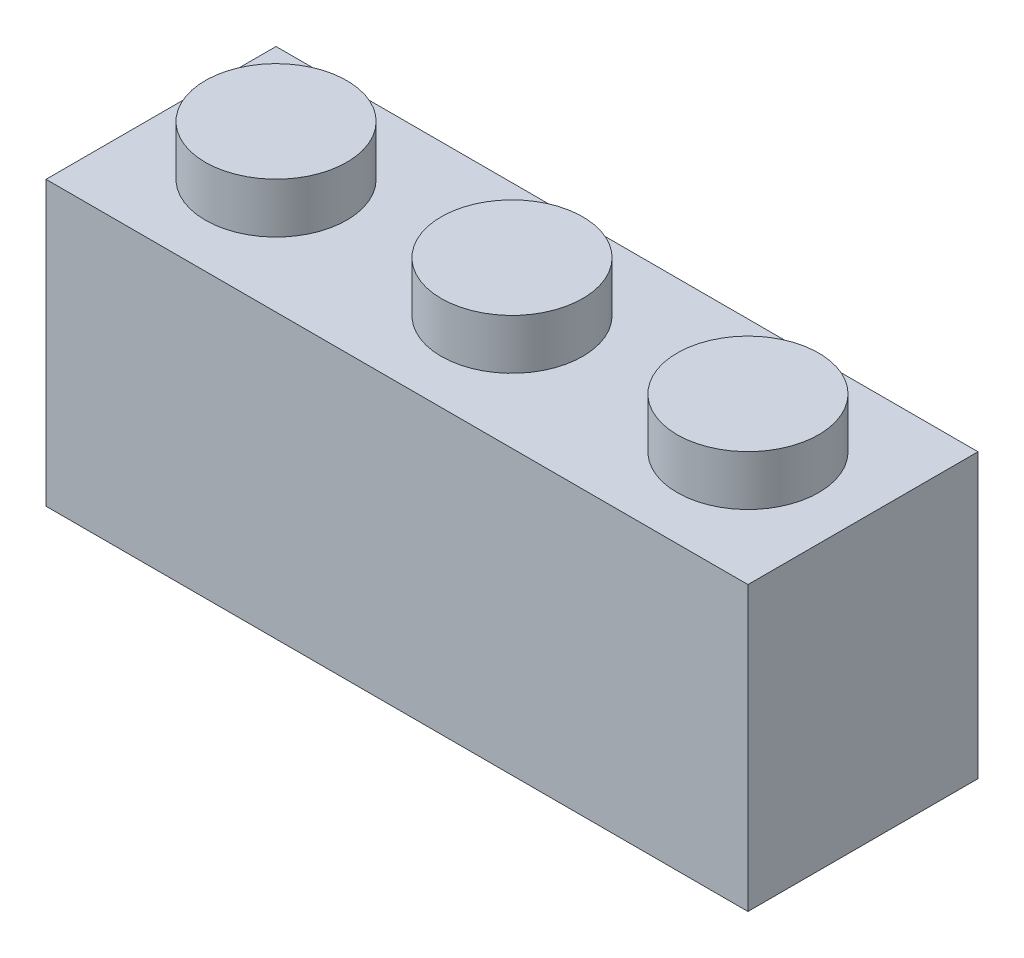
SolidWorks part; units mm, degrees
ref_plane "Спереди" through (0, 0, 0) normal (0, 0, 1) x (1, 0, 0)
ref_plane "Сверху" through (0, 0, 0) normal (0, 1, 0) x (1, 0, 0)
ref_plane "Справа" through (0, 0, 0) normal (1, 0, 0) x (0, 0, -1)
sketch "Эскиз1" plane through (0, 0, 0) normal (0, 1, 0) x (1, 0, 0)
  line L1 (11.9, -3.9) -> (-11.9, -3.9)
  line L2 (11.9, -3.9) -> (11.9, 3.9)
  line L3 (11.9, 3.9) -> (-11.9, 3.9)
  line L4 (-11.9, -3.9) -> (-11.9, 3.9)
  line L5 (11.9, -3.9) -> (-11.9, 3.9) construction
  line L6 (11.9, 3.9) -> (-11.9, -3.9) construction
  point P0 (0, 0)
  dimension "D1" = 23.8
  dimension "D2" = 7.8
extrude "Бобышка-Вытянуть1" add sketch "Эскиз1" along normal blind 9.6
sketch "Эскиз2" plane through (0, 9.6, 0) normal (0, 1, 0) x (1, 0, 0)
  line L0 (-11.9, 3.9) -> (-11.9, -3.9) construction
  line L1 (-11.9, -3.9) -> (11.9, -3.9) construction
  circle A0 centre (-8, 0) radius 2.4
  circle A1 centre (0, 0) radius 2.4
  circle A2 centre (8, 0) radius 2.4
  dimension "D1" = 3.9
  dimension "D2" = 3.9
  dimension "D3" = 3
extrude "Бобышка-Вытянуть2" add sketch "Эскиз2" along normal blind 1.7
sketch "Эскиз3" plane through (0, 0, 0) normal (0, -1, 0) x (1, 0, 0)
  line L0 (-11.9, -3.9) -> (-11.9, 3.9) construction
  line L1 (11.9, -3.9) -> (-11.9, -3.9) construction
  circle A0 centre (-8, 0) radius 2.5
  circle A1 centre (0, 0) radius 2.5
  circle A2 centre (8, 0) radius 2.5
  dimension "D1" = 3.9
  dimension "D2" = 3.9
  dimension "D3" = 3
extrude "Вырез-Вытянуть1" cut sketch "Эскиз3" against normal blind 1.8
